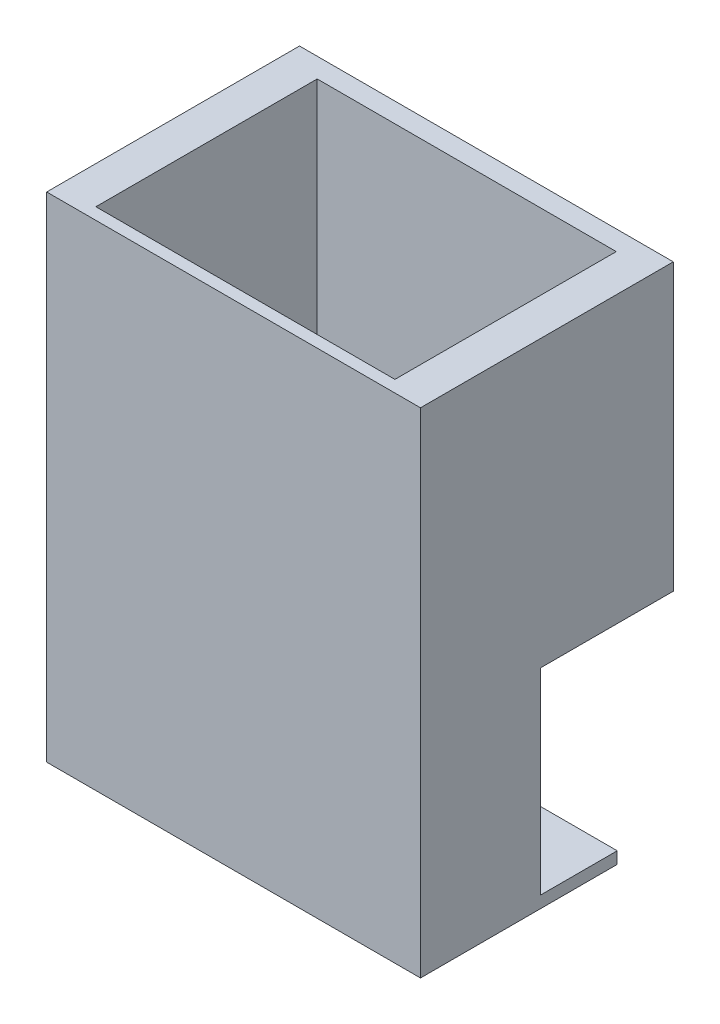
SolidWorks part; units mm, degrees
ref_plane "Front Plane" through (0, 0, 0) normal (0, 0, 1) x (1, 0, 0)
ref_plane "Top Plane" through (0, 0, 0) normal (0, 1, 0) x (1, 0, 0)
ref_plane "Right Plane" through (0, 0, 0) normal (1, 0, 0) x (0, 0, -1)
sketch "Sketch1" plane through (0, 0, 0) normal (0, 1, 0) x (1, 0, 0)
  line L1 (0, 0) -> (48.26, 0)
  line L2 (0, 0) -> (0, 25.4)
  line L3 (0, 25.4) -> (48.26, 25.4)
  line L4 (48.26, 0) -> (48.26, 25.4)
  dimension "D1" = 48.26
  dimension "D2" = 25.4
extrude "Boss-Extrude1" add sketch "Sketch1" along normal blind 1.524 contours L3 L4 L1 L2
sketch "Sketch2" plane through (0, 1.524, 0) normal (0, 1, 0) x (1, 0, 0)
  line L0 (0, 15.494) -> (4.826, 15.494)
  line L2 (4.826, 15.494) -> (4.826, 1.524)
  line L3 (4.826, 1.524) -> (43.434, 1.524)
  line L4 (43.434, 1.524) -> (43.434, 15.494)
  line L5 (43.434, 15.494) -> (48.26, 15.494)
  line L6 (48.26, 15.494) -> (48.26, 0)
  line L7 (48.26, 0) -> (48.26, 25.4) construction
  line L8 (48.26, 0) -> (0, 0)
  line L9 (0, 0) -> (0, 15.494)
  dimension "D1" = 1.524
  dimension "D2" = 4.826
  dimension "D3" = 4.826
  dimension "D4" = 13.97
extrude "Boss-Extrude2" add sketch "Sketch2" along normal blind 36.83
sketch "Sketch3" plane through (0, 1.524, 0) normal (0, 1, 0) x (1, 0, 0)
  line L0 (43.434, 1.524) -> (4.826, 1.524) construction
  line L1 (4.826, 15.494) -> (8.001, 15.494)
  line L2 (4.826, 15.494) -> (4.826, 12.319)
  line L3 (4.826, 12.319) -> (8.001, 12.319)
  line L4 (8.001, 15.494) -> (8.001, 12.319)
  line L5 (43.434, 15.494) -> (40.259, 15.494)
  line L6 (43.434, 15.494) -> (43.434, 12.319)
  line L7 (43.434, 12.319) -> (40.259, 12.319)
  line L8 (40.259, 15.494) -> (40.259, 12.319)
  dimension "D1" = 10.795
  dimension "D2" = 3.175
extrude "Boss-Extrude3" add sketch "Sketch3" along normal up to surface (36.83 mm away) up to face at (24.13, 38.354, -8.128)
sketch "Sketch4" plane through (0, 0, -15.494) normal (0, 0, -1) x (-1, 0, 0)
  line L0 (-40.259, 38.354) -> (-36.195, 1.524)
  line L1 (0, 1.524) -> (-48.26, 1.524) construction
  line L2 (-36.195, 1.524) -> (-40.259, 1.524)
  line L3 (-40.259, 1.524) -> (-40.259, 38.354)
  line L4 (-8.001, 38.354) -> (-12.065, 1.524)
  line L5 (-12.065, 1.524) -> (-8.001, 1.524)
  line L6 (-8.001, 1.524) -> (-8.001, 38.354)
  dimension "D1" = 24.13
extrude "Boss-Extrude4" add sketch "Sketch4" against normal up to surface (3.175 mm away) up to face at (41.8465, 19.939, -12.319)
sketch "Sketch5" plane through (0, 0, -15.494) normal (0, 0, -1) x (-1, 0, 0)
  line L0 (-48.26, 1.524) -> (-36.195, 1.524) construction
  line L1 (-48.26, 38.354) -> (-43.434, 38.354)
  line L2 (-48.26, 38.354) -> (-48.26, 26.924)
  line L3 (-48.26, 26.924) -> (-43.434, 26.924)
  line L4 (-43.434, 38.354) -> (-43.434, 26.924)
  line L5 (0, 38.354) -> (-4.826, 38.354)
  line L6 (0, 38.354) -> (0, 26.924)
  line L7 (0, 26.924) -> (-4.826, 26.924)
  line L8 (-4.826, 38.354) -> (-4.826, 26.924)
  dimension "D1" = 25.4
extrude "Boss-Extrude5" add sketch "Sketch5" along normal blind 14.605
sketch "Sketch7" plane through (48.26, 0, 0) normal (1, 0, 0) x (0, 0, -1)
  line L1 (30.099, 38.354) -> (32.639, 38.354)
  line L2 (30.099, 38.354) -> (30.099, 26.924)
  line L3 (30.099, 26.924) -> (32.639, 26.924)
  line L4 (32.639, 38.354) -> (32.639, 26.924)
  dimension "D1" = 2.54
extrude "Boss-Extrude6" add sketch "Sketch7" against normal up to surface (48.26 mm away) up to face at (0, 16.7005, -17.7482)
sketch "Sketch8" plane through (0, 38.354, 0) normal (0, 1, 0) x (1, 0, 0)
  line L1 (0, 32.639) -> (48.26, 32.639)
  line L2 (0, 32.639) -> (0, 0)
  line L3 (0, 0) -> (48.26, 0)
  line L4 (48.26, 32.639) -> (48.26, 0)
  line L5 (43.434, 1.524) -> (4.826, 1.524)
  line L6 (43.434, 1.524) -> (43.434, 30.099)
  line L7 (43.434, 30.099) -> (4.826, 30.099)
  line L8 (4.826, 1.524) -> (4.826, 30.099)
extrude "Boss-Extrude7" add sketch "Sketch8" along normal blind 25.4
